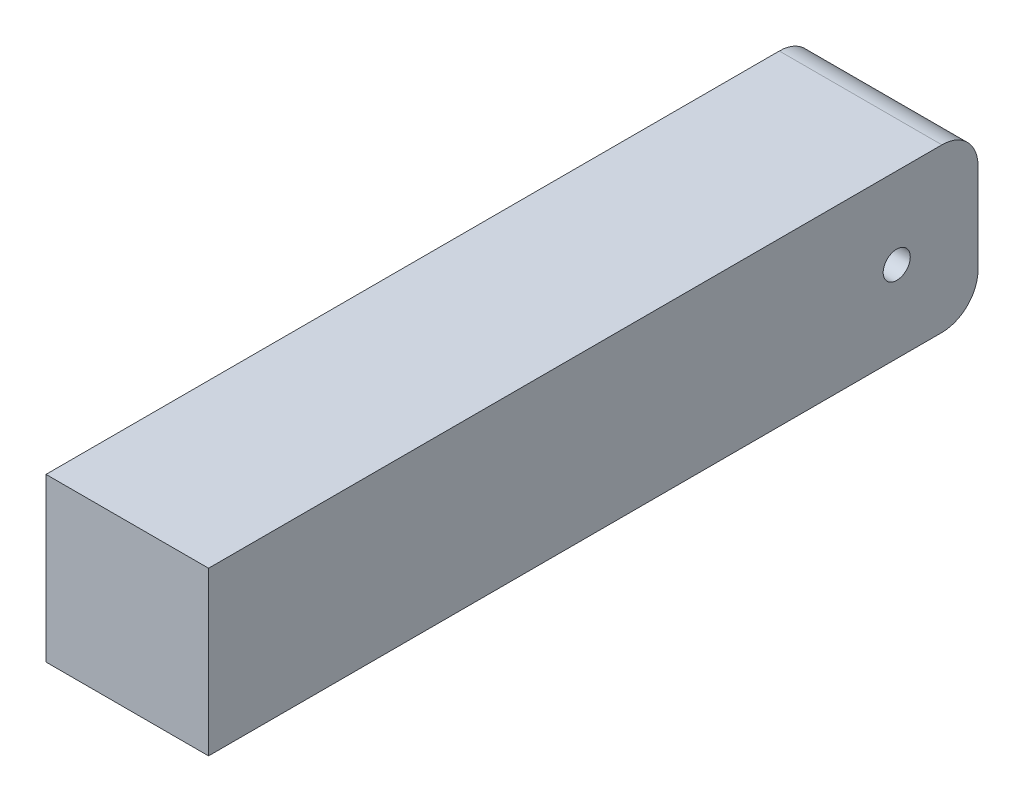
SolidWorks part; units mm, degrees
material "Custom Plastic"
ref_plane "Front Plane" through (0, 0, 0) normal (0, 0, 1) x (1, 0, 0)
ref_plane "Top Plane" through (0, 0, 0) normal (0, 1, 0) x (1, 0, 0)
ref_plane "Right Plane" through (0, 0, 0) normal (1, 0, 0) x (0, 0, -1)
sketch "Sketch1" plane through (0, 0, 0) normal (1, 0, 0) x (0, 0, -1)
  line L1 (0, 0) -> (85.2, 0)
  line L2 (0, 0) -> (0, 18)
  line L3 (0, 18) -> (85.2, 18)
  line L4 (85.2, 0) -> (85.2, 18)
  circle A0 centre (76.2, 9) radius 1.5
  point P7 (85.2, 9)
  point P8 (0, 0)
  dimension "D4" = 3
  dimension "D1" = 18
  dimension "D2" = 85.2
  dimension "D3" = 9
extrude "Boss-Extrude1" add sketch "Sketch1" along normal blind 18
sketch "Sketch2" plane through (0, 0, 0) normal (-1, 0, 0) x (0, 0, 1)
  circle A0 centre (-76.2, 9) radius 3
  dimension "D1" = 6
extrude "Cut-Extrude1" cut sketch "Sketch2" against normal blind 8
fillet "Fillet1" radius 4 2 edges at (9, 0, -85.2) (9, 18, -85.2)
